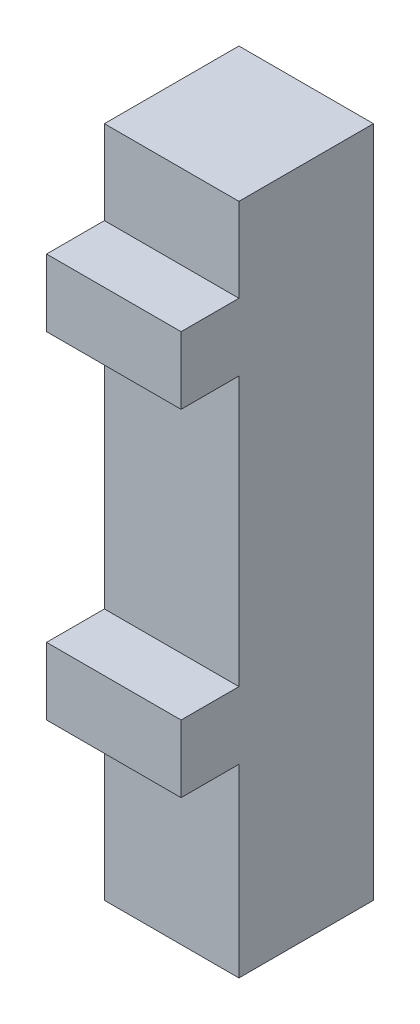
SolidWorks part; units mm, degrees
ref_plane "Front Plane" through (0, 0, 0) normal (0, 0, 1) x (1, 0, 0)
ref_plane "Top Plane" through (0, 0, 0) normal (0, 1, 0) x (1, 0, 0)
ref_plane "Right Plane" through (0, 0, 0) normal (1, 0, 0) x (0, 0, -1)
sketch "Sketch1" plane through (0, 0, 0) normal (0, 1, 0) x (1, 0, 0)
  line L1 (-30.6224, 20.2905) -> (69.3776, 20.2905)
  line L2 (-30.6224, 20.2905) -> (-30.6224, -79.7095)
  line L3 (-30.6224, -79.7095) -> (69.3776, -79.7095)
  line L4 (69.3776, 20.2905) -> (69.3776, -79.7095)
  dimension "D1" = 100
  dimension "D2" = 100
extrude "Boss-Extrude1" add sketch "Sketch1" along normal blind 500
sketch "Sketch2" plane through (0, 0, 79.7095) normal (0, 0, 1) x (1, 0, 0)
  line L0 (-30.6224, 387.5882) -> (-30.6224, 137.5882)
  line L1 (-30.6224, 137.5882) -> (69.3776, 137.5882)
  line L2 (69.3776, 137.5882) -> (69.3776, 187.5882)
  line L3 (69.3776, 187.5882) -> (-30.6224, 187.5882)
  line L4 (-30.6224, 187.5882) -> (-30.6224, 137.5882)
  line L5 (69.3776, 500) -> (69.3776, 0) construction
  line L6 (69.3776, 387.5882) -> (-30.6224, 387.5882)
  line L7 (-30.6224, 500) -> (-30.6224, 0) construction
  line L8 (-30.6224, 387.5882) -> (-30.6224, 437.5882)
  line L9 (-30.6224, 437.5882) -> (69.3776, 437.5882)
  line L10 (69.3776, 437.5882) -> (69.3776, 387.5882)
  line M8 (69.3776, 0) -> (69.3776, 500)
  line M10 (-30.6224, 500) -> (-30.6224, 0)
  dimension "D1" = 250
  dimension "D2" = 50
  dimension "D3" = 100
  dimension "D4" = 50
extrude "Boss-Extrude2" add sketch "Sketch2" along normal blind 43 contours L9 L6 M10 M8 | L1 L2 L3 L4
